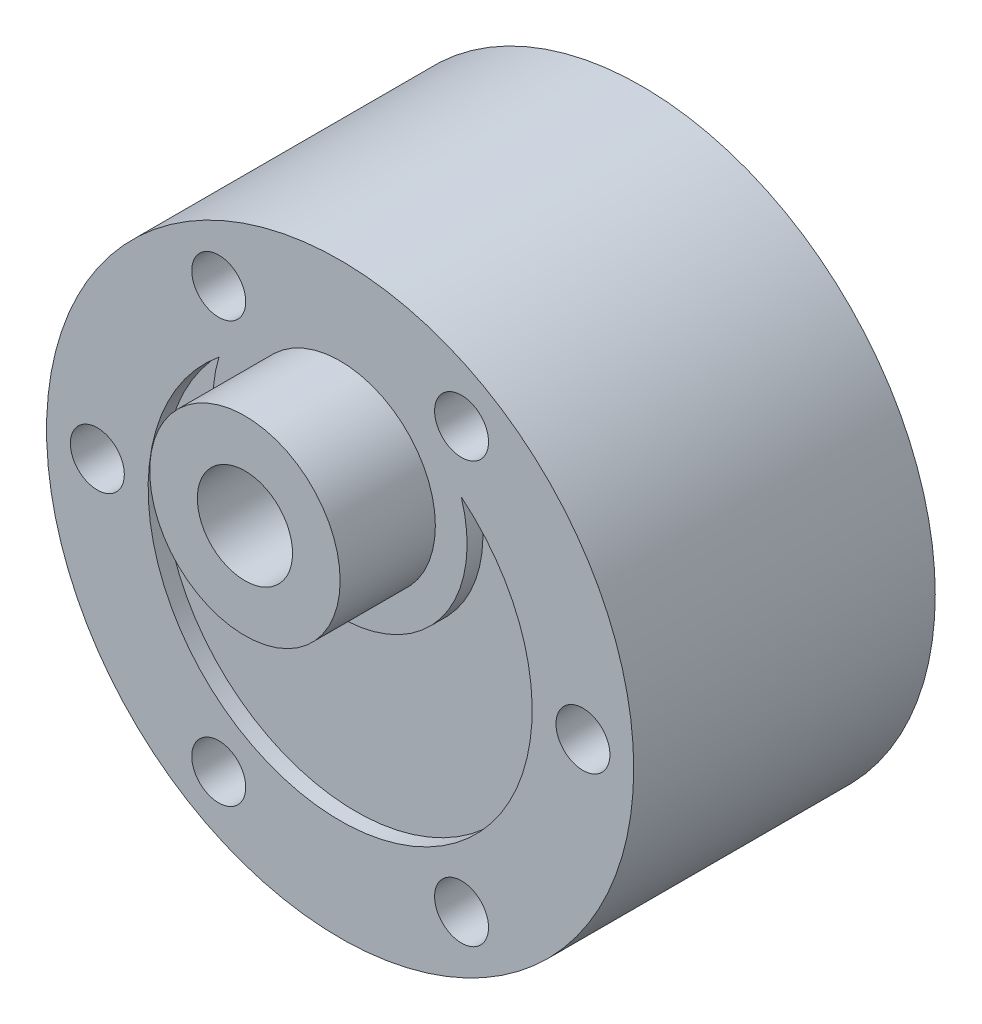
SolidWorks part; units mm, degrees
ref_plane "Front Plane" through (0, 0, 0) normal (0, 0, 1) x (1, 0, 0)
ref_plane "Top Plane" through (0, 0, 0) normal (0, 1, 0) x (1, 0, 0)
ref_plane "Right Plane" through (0, 0, 0) normal (1, 0, 0) x (0, 0, -1)
sketch "Sketch1" plane through (0, 0, 0) normal (0, 0, 1) x (1, 0, 0)
  circle A0 centre (0, 0) radius 18.5
  dimension "D1" = 37
extrude "Boss-Extrude1" add sketch "Sketch1" along normal blind 19
sketch "Sketch4" plane through (0, 0, 19) normal (0, 0, 1) x (1, 0, 0)
  circle A0 centre (0, 7) radius 6
  circle A1 centre (0, 0) radius 18.5 construction
  dimension "D1" = 12
  dimension "D2" = 7
extrude "Boss-Extrude4" add sketch "Sketch4" along normal blind 6
sketch "Sketch8" plane through (0, 0, 19) normal (0, 0, 1) x (1, 0, 0)
  circle A0 centre (0, 0) radius 18.5 construction
  arc A1 (7.6358, 9.3864) -> (-7.6358, 9.3864) centre (0, 0) cw
  arc A3 (-7.6358, 9.3864) -> (7.6358, 9.3864) centre (0, 7) ccw
  dimension "D1" = 8
  dimension "D2" = 12.1
  dimension "D3" = 6.4
  dimension "D4" = 7
extrude "Cut-Extrude2" cut sketch "Sketch8" against normal blind 1
hole_wizard "Taladro de margen para M31" positions "Sketch9" profile "Sketch10" hole size "M3" standard "Ansi Metric"
sketch "Sketch9" plane through (0, 0, 19) normal (0, 0, 1) x (1, 0, 0)
  line L0 (0, 0) -> (0, -7.0626) construction
  line L2 (7.65, -13.2502) -> (0, 0) construction
  line L3 (-7.65, -13.2502) -> (0, 0) construction
  line L5 (-15.3, 0) -> (0, 0) construction
  line L6 (0, 0) -> (-7.65, 13.2502) construction
  line L8 (0, 0) -> (15.3, 0) construction
  line L9 (0, 0) -> (7.65, 13.2502) construction
  circle A0 centre (0, 0) radius 15.3
  point P0 (7.65, -13.2502)
  point P23 (-7.65, -13.2502)
  point P25 (-15.3, 0)
  point P27 (-7.65, 13.2502)
  point P32 (15.3, 0)
  point P60 (7.65, 13.2502)
  dimension "D1" = 15.3
  dimension "D2" = 30
  dimension "D3" = 30
  dimension "D4" = 60
  dimension "D5" = 60
  dimension "D6" = 60
  dimension "D7" = 60
sketch "Sketch10" plane through (7.65, -13.2502, 19) normal (1, 0, 0) x (0, -1, 0)
  line L0 (0, 0) -> (0, 7.0215)
  line L1 (0, 7.0215) -> (1.7, 6)
  line L2 (1.7, 6) -> (1.7, 0)
  line L5 (1.7, 0) -> (0, 0)
  line L10 (0, 7.0215) -> (-1.7, 6) construction
  line L11 (0, -6.35) -> (0, 107.95) construction
  dimension "Hole Dia." = 3.4
  dimension "Hole Depth" = 6
  dimension "Drill Angle" = 118
sketch "Croquis1" plane through (0, 0, 0) normal (0, 0, -1) x (-1, 0, 0)
  circle A0 centre (0, 0) radius 18
extrude "Cortar-Extruir2" cut sketch "Croquis1" against normal blind 12
sketch "Croquis2" plane through (0, 0, 25) normal (0, 0, 1) x (1, 0, 0)
  circle A0 centre (0, 7) radius 3
extrude "Cortar-Extruir3" cut sketch "Croquis2" against normal up to next
sketch "Croquis3" plane through (0, 0, 0) normal (0, 0, -1) x (-1, 0, 0)
  circle A0 centre (0, 0) radius 18
extrude "Saliente-Extruir1" add sketch "Croquis3" against normal blind 0.5
sketch "Sketch11" plane through (0, 0, 0) normal (0, 0, -1) x (-1, 0, 0)
  circle A0 centre (0, 0) radius 2
extrude "Cut-Extrude3" cut sketch "Sketch11" against normal blind 10
sketch "Sketch12" plane through (0, 0, 0) normal (0, 0, -1) x (-1, 0, 0)
  line L0 (0, 0) -> (0, -15) construction
  line L1 (-6.25, -14.25) -> (6.25, -14.25)
  line L2 (-6.25, -14.25) -> (-6.25, -15.75)
  line L3 (-6.25, -15.75) -> (6.25, -15.75)
  line L4 (6.25, -14.25) -> (6.25, -15.75)
  line L5 (-6.25, -14.25) -> (6.25, -15.75) construction
  line L6 (-6.25, -15.75) -> (6.25, -14.25) construction
  point P0 (0, -15)
  dimension "D1" = 1.5
  dimension "D2" = 12.5
  dimension "D3" = 15
extrude "Cut-Extrude4" cut sketch "Sketch12" against normal blind 0.15
sketch "Sketch13" plane through (0, 0, 0) normal (0, 0, -1) x (-1, 0, 0)
  circle A1 centre (0, 0) radius 6
  dimension "D2" = 12
extrude "Cut-Extrude5" cut sketch "Sketch13" against normal blind 10
sketch "Sketch14" plane through (0, 0, 12) normal (0, 0, -1) x (-1, 0, 0)
  line L0 (0, 7) -> (0, -5.15) construction
  circle A0 centre (0, -5.15) radius 2
  circle A1 centre (0, -5.15) radius 2.25
  dimension "D1" = 4
  dimension "D3" = 4.5
  dimension "D2" = 12.15
extrude "Boss-Extrude5" add sketch "Sketch14" along normal blind 1
